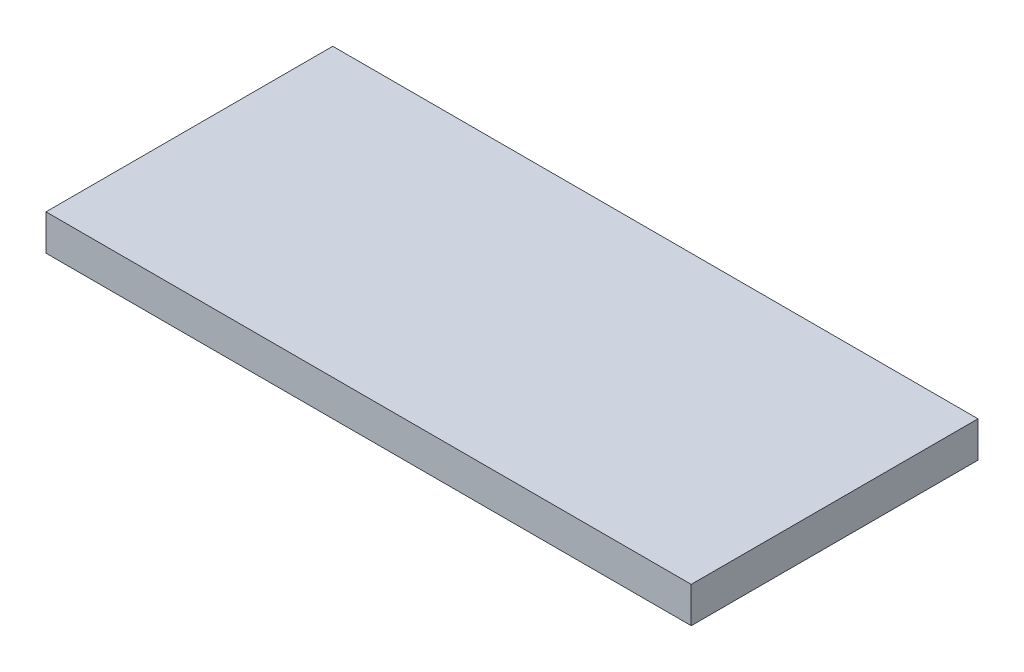
SolidWorks part; units mm, degrees
ref_plane "정면" through (0, 0, 0) normal (0, 0, 1) x (1, 0, 0)
ref_plane "윗면" through (0, 0, 0) normal (0, 1, 0) x (1, 0, 0)
ref_plane "우측면" through (0, 0, 0) normal (1, 0, 0) x (0, 0, -1)
sketch "스케치1" plane through (0, 0, 0) normal (0, 1, 0) x (1, 0, 0)
  line L1 (-450, 200) -> (450, 200)
  line L2 (-450, 200) -> (-450, -200)
  line L3 (-450, -200) -> (450, -200)
  line L4 (450, 200) -> (450, -200)
  line L5 (-450, 200) -> (450, -200) construction
  line L6 (-450, -200) -> (450, 200) construction
  point P0 (0, 0)
  dimension "D1" = 900
  dimension "D2" = 400
extrude "900x300" add sketch "스케치1" along normal blind 50
